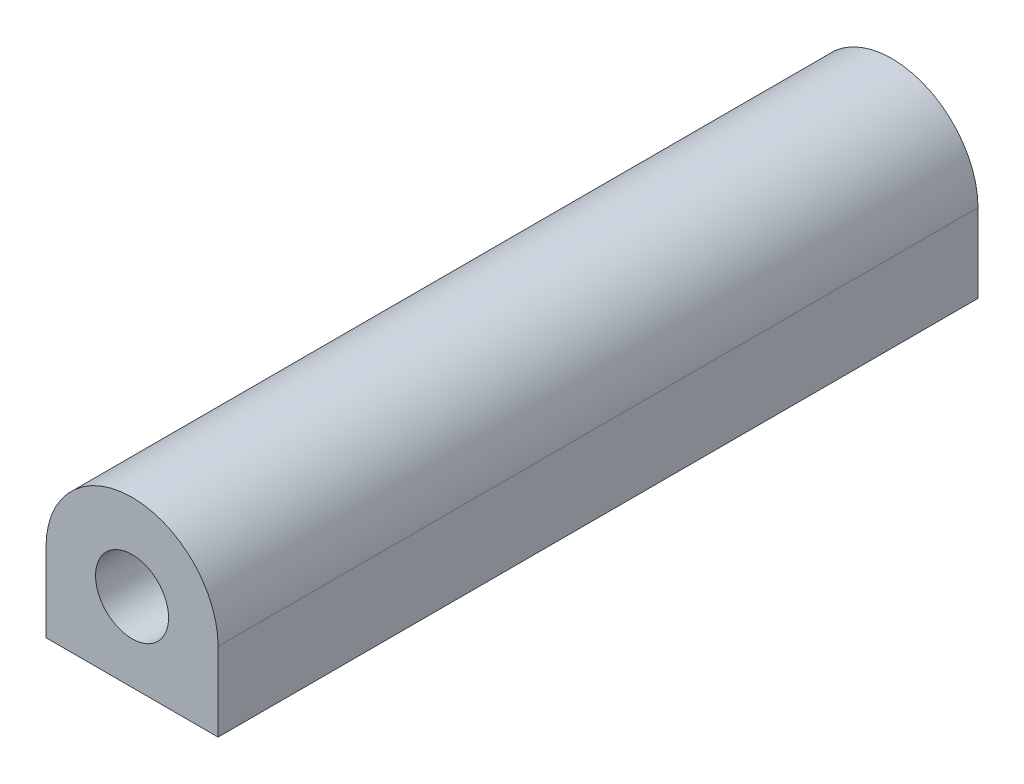
SolidWorks part; units mm, degrees
ref_plane "Front Plane" through (0, 0, 0) normal (0, 0, 1) x (1, 0, 0)
ref_plane "Top Plane" through (0, 0, 0) normal (0, 1, 0) x (1, 0, 0)
ref_plane "Right Plane" through (0, 0, 0) normal (1, 0, 0) x (0, 0, -1)
sketch "Sketch2" plane through (0, 0, 0) normal (0, 0, 1) x (1, 0, 0)
  circle A0 centre (0, 0) radius 1.475
  circle A1 centre (0, 0) radius 3.475
  dimension "D1" = 2.95
  dimension "D2" = 2
extrude "Boss-Extrude2" add sketch "Sketch2" along normal blind 30.6846 contours A1
sketch "Sketch3" plane through (0, 0, 30.6846) normal (0, 0, 1) x (1, 0, 0)
  circle A0 centre (0, 0) radius 1.475
  dimension "D1" = 2.95
extrude "Cut-Extrude1" cut sketch "Sketch3" against normal blind 10
sketch "Sketch4" plane through (0, 0, 0) normal (0, 0, -1) x (-1, 0, 0)
  circle A0 centre (0, 0) radius 1.475
  dimension "D1" = 2.95
extrude "Cut-Extrude2" cut sketch "Sketch4" against normal blind 10
sketch "Sketch5" plane through (0, 0, 0) normal (0, 0, -1) x (-1, 0, 0)
  line L0 (3.475, 0) -> (3.475, 1.469)
  line L2 (-3.475, 0) -> (3.475, 0)
  line L3 (-3.475, 0) -> (-3.475, -3.475)
  line L4 (-3.475, -3.475) -> (3.475, -3.475)
  line L5 (3.475, 0) -> (3.475, -3.475)
  circle A0 centre (0, 0) radius 3.475
  circle M7 centre (0, 0) radius 3.475
extrude "Boss-Extrude3" add sketch "Sketch5" against normal up to surface (30.6846 mm away) contours L3 L4 M7 | L5 L4 M7 up to face at (1.475, 0, 30.6846)
sketch "Sketch6" plane through (0, -3.475, 0) normal (0, -1, 0) x (-1, 0, 0)
  line L0 (3.475, -30.6846) -> (3.475, 0) construction
  line L1 (3.475, -30.6846) -> (-3.475, -30.6846)
  line L2 (3.475, -30.6846) -> (3.475, 0)
  line L3 (3.475, 0) -> (-3.475, 0)
  line L4 (-3.475, -30.6846) -> (-3.475, 0)
  line L5 (-3.475, -30.6846) -> (3.475, -30.6846) construction
extrude "Cut-Extrude3" cut sketch "Sketch6" against normal blind 0.3
